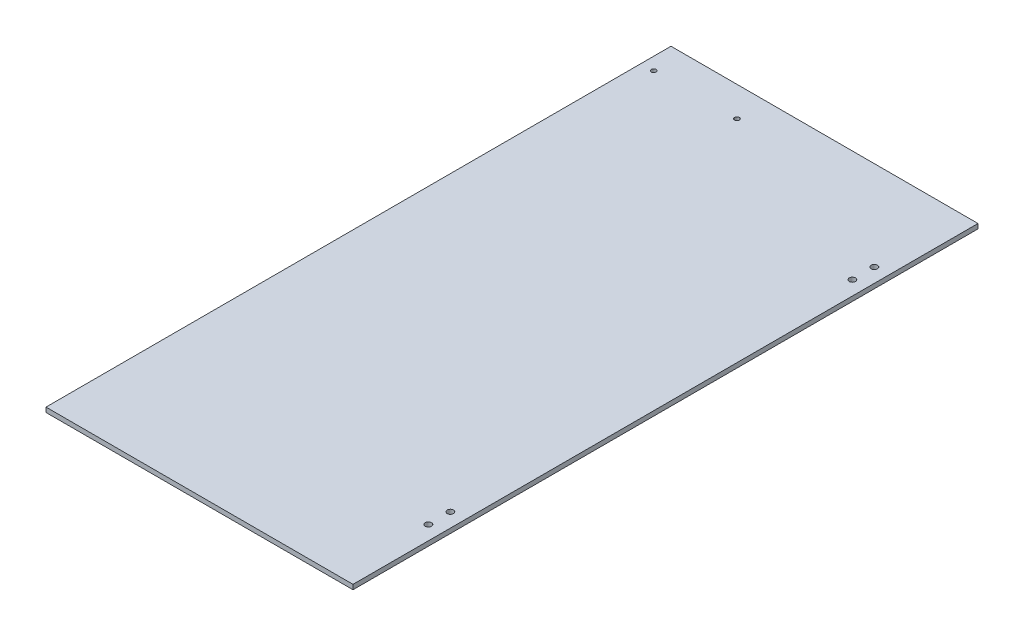
SolidWorks part; units mm, degrees
ref_plane "Front Plane" through (0, 0, 0) normal (0, 0, 1) x (1, 0, 0)
ref_plane "Top Plane" through (0, 0, 0) normal (0, 1, 0) x (1, 0, 0)
ref_plane "Right Plane" through (0, 0, 0) normal (1, 0, 0) x (0, 0, -1)
sketch "Sketch1" plane through (0, -196.7989, 0) normal (0, 1, 0) x (1, 0, 0)
  line L0 (105.7892, -780.1429) -> (105.7892, -801.3855) construction
  line L1 (105.7892, -389.6201) -> (105.7892, -789.6201) construction
  line L2 (108.7892, -789.6201) -> (103.3802, -789.6201) construction
  line L3 (-327.2108, -789.6201) -> (104.7892, -789.6201) construction
  line L4 (-87.2108, -789.6201) -> (-87.2108, -389.6201)
  line L5 (105.7892, -789.6201) -> (-87.2108, -789.6201)
  line L6 (105.7892, -789.6201) -> (105.7892, -389.6201)
  line L7 (105.7892, -389.6201) -> (-87.2108, -389.6201)
  dimension "D1" = 193
extrude "Boss-Extrude1" add sketch "Sketch1" along normal blind 3
sketch "Sketch2" plane through (0, -193.7989, 0) normal (0, 1, 0) x (1, 0, 0)
  line L1 (105.7892, -389.6201) -> (-87.2108, -389.6201) construction
  line L2 (-87.2108, -389.6201) -> (-87.2108, -789.6201) construction
  circle A15 centre (-78.7108, -409.6201) radius 1.5
  circle A16 centre (-25.7108, -409.6201) radius 1.5
  dimension "D2" = 8.5
  dimension "D1" = 2
  dimension "D3" = 20
  dimension "D4" = 53
extrude "Cut-Extrude1" cut sketch "Sketch2" against normal blind 10
sketch "Sketch3" plane through (0, -196.7989, 0) normal (0, -1, 0) x (1, 0, 0)
  line L0 (99.7892, 789.6201) -> (99.7892, 389.6201) construction
  line L1 (-87.2108, 789.6201) -> (105.7892, 789.6201) construction
  line L2 (105.7892, 389.6201) -> (-87.2108, 389.6201) construction
  line L3 (105.7892, 789.6201) -> (105.7892, 389.6201) construction
  line L4 (99.7892, 589.6201) -> (-87.2108, 589.6201) construction
  line L5 (-87.2108, 389.6201) -> (-87.2108, 789.6201) construction
  circle A0 centre (99.7892, 731.6201) radius 2
  circle A1 centre (99.7892, 717.6201) radius 2
  circle A2 centre (99.7892, 461.6201) radius 2
  circle A3 centre (99.7892, 447.6201) radius 2
  dimension "D2" = 4
  dimension "D3" = 4
  dimension "D4" = 14
  dimension "D5" = 58
  dimension "D1" = 6
extrude "Cut-Extrude2" cut sketch "Sketch3" against normal blind 10
sketch "Sketch4" plane through (0, 0, 789.6201) normal (0, 0, 1) x (1, 0, 0)
  line L1 (122.8139, -226.4603) -> (-125.7768, -226.4603)
  line L2 (122.8139, -226.4603) -> (122.8139, -183.1503)
  line L3 (122.8139, -183.1503) -> (-125.7768, -183.1503)
  line L4 (-125.7768, -226.4603) -> (-125.7768, -183.1503)
extrude "Cut-Extrude3" cut sketch "Sketch4" against normal blind 1
sketch "Sketch5" plane through (0, 0, 389.6201) normal (0, 0, -1) x (-1, 0, 0)
  line L1 (-186.1594, -136.0782) -> (130.0401, -136.0782)
  line L2 (-186.1594, -136.0782) -> (-186.1594, -218.0395)
  line L3 (-186.1594, -218.0395) -> (130.0401, -218.0395)
  line L4 (130.0401, -136.0782) -> (130.0401, -218.0395)
extrude "Cut-Extrude4" cut sketch "Sketch5" against normal blind 1
surface "Surface-Offset1" parameters "D1"=0
thicken "Thicken1" thickness 3 parameters "D1"=3
sketch "Sketch6" plane through (-87.2108, 0, 0) normal (-1, 0, 0) x (0, 0, 1)
  line L1 (356.2226, -134.403) -> (813.2743, -134.403)
  line L2 (356.2226, -134.403) -> (356.2226, -251.3232)
  line L3 (356.2226, -251.3232) -> (813.2743, -251.3232)
  line L4 (813.2743, -134.403) -> (813.2743, -251.3232)
extrude "Cut-Extrude5" cut sketch "Sketch6" against normal blind 0.5
